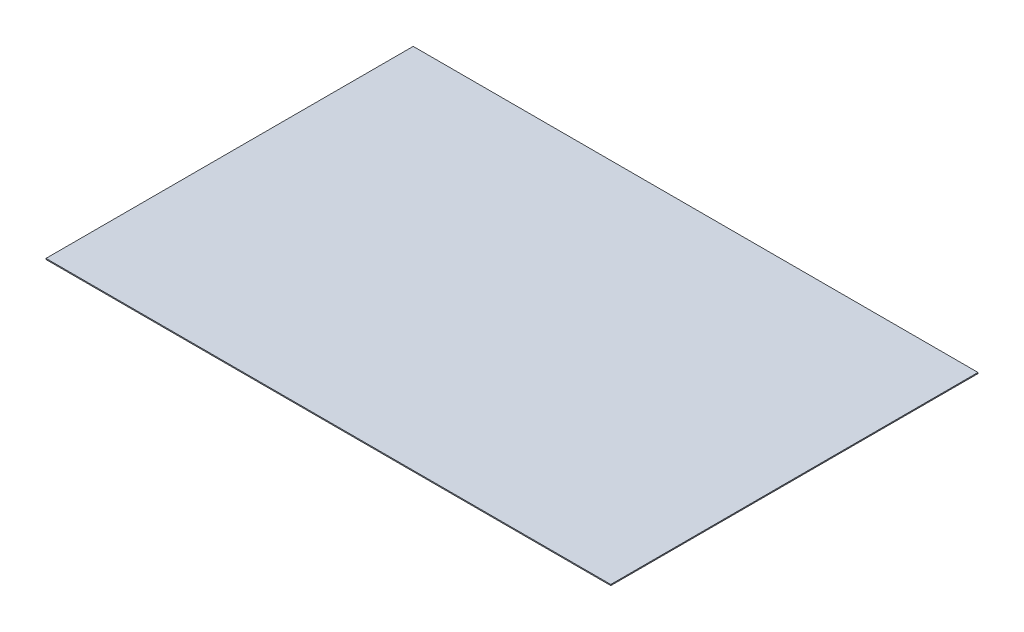
SolidWorks part; units mm, degrees
ref_plane "Front Plane" through (0, 0, 0) normal (0, 0, 1) x (1, 0, 0)
ref_plane "Top Plane" through (0, 0, 0) normal (0, 1, 0) x (1, 0, 0)
ref_plane "Right Plane" through (0, 0, 0) normal (1, 0, 0) x (0, 0, -1)
sketch "Sketch1" plane through (0, 0, 0) normal (0, 1, 0) x (1, 0, 0)
  line L1 (468.6899, -204.7339) -> (-620.3101, -204.7339)
  line L2 (468.6899, -204.7339) -> (468.6899, 503.2661)
  line L3 (468.6899, 503.2661) -> (-620.3101, 503.2661)
  line L4 (-620.3101, -204.7339) -> (-620.3101, 503.2661)
  dimension "D1" = 708
  dimension "D2" = 1089
extrude "Boss-Extrude1" add sketch "Sketch1" along normal blind 2
